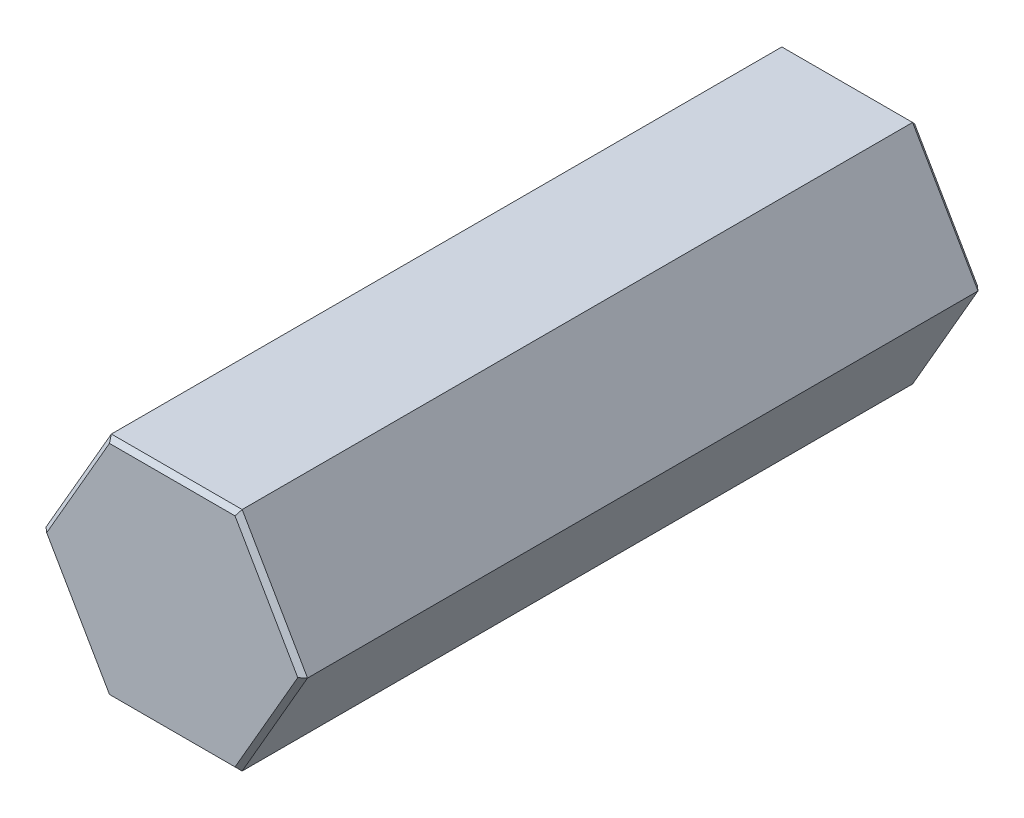
SolidWorks part; units mm, degrees
ref_plane "Front Plane" through (0, 0, 0) normal (0, 0, 1) x (1, 0, 0)
ref_plane "Top Plane" through (0, 0, 0) normal (0, 1, 0) x (1, 0, 0)
ref_plane "Right Plane" through (0, 0, 0) normal (1, 0, 0) x (0, 0, -1)
ref_plane "Plane1" through (0, 0, 0) normal (0, 0, -1) x (-1, 0, 0)
sketch "Sketch1" plane through (0, 0, 0) normal (0, 0, -1) x (-1, 0, 0)
  line L0 (3.6662, 6.35) -> (-3.6662, 6.35)
  line L1 (-3.6662, 6.35) -> (-7.3323, 0)
  line L2 (-7.3323, 0) -> (-3.6662, -6.35)
  line L3 (-3.6662, -6.35) -> (3.6662, -6.35)
  line L4 (3.6662, -6.35) -> (7.3323, 0)
  line L5 (7.3323, 0) -> (3.6662, 6.35)
extrude "Boss-Extrude1" add sketch "Sketch1" against normal blind 38.1
chamfer "Chamfer1" distance 0.254 angle 45 12 edges at (0, -6.35, 0) (5.4993, -3.175, 0) (-5.4993, -3.175, 0) (5.4993, 3.175, 0) (-5.4993, 3.175, 0) (0, 6.35, 0) (-5.4993, -3.175, 38.1) (0, -6.35, 38.1) (-5.4993, 3.175, 38.1) (5.4993, -3.175, 38.1) (0, 6.35, 38.1) (5.4993, 3.175, 38.1)
